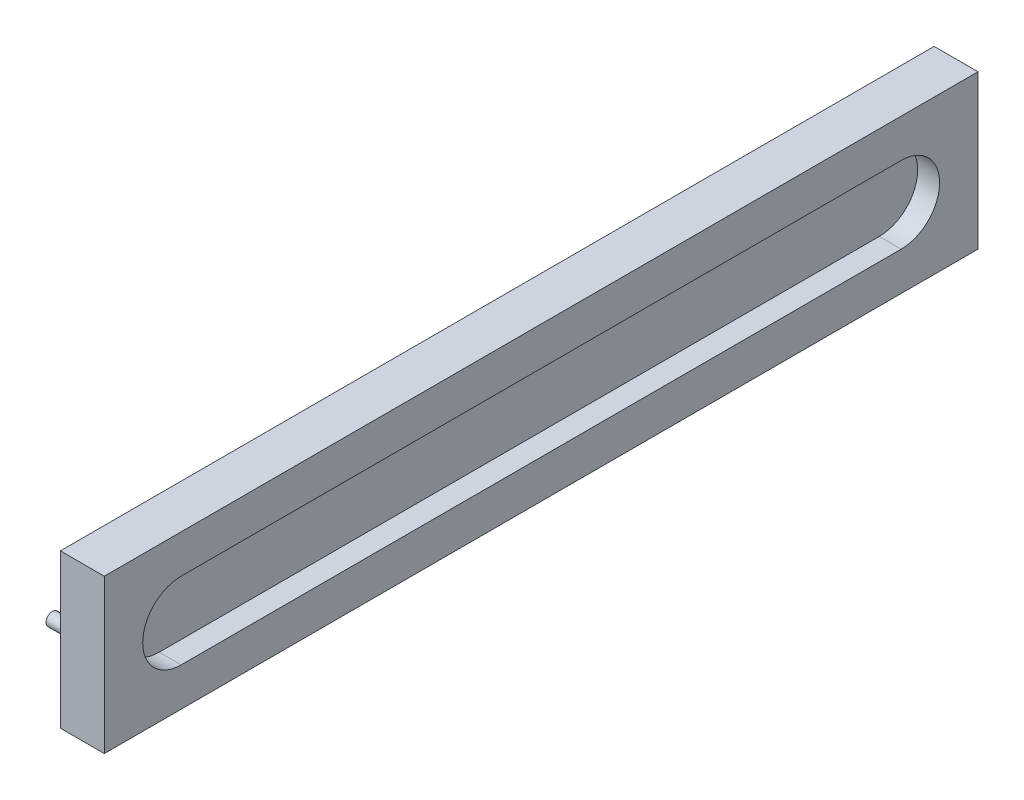
SolidWorks part; units mm, degrees
ref_plane "Front" through (0, 0, 0) normal (0, 0, 1) x (1, 0, 0)
ref_plane "Top" through (0, 0, 0) normal (0, 1, 0) x (1, 0, 0)
ref_plane "Right" through (0, 0, 0) normal (1, 0, 0) x (0, 0, -1)
sketch "Sketch2" plane through (0, 0, 0) normal (1, 0, 0) x (0, 0, -1)
  line L0 (0, 35) -> (17.5, 35) construction
  line L1 (0, 0) -> (398.1006, 0)
  line L2 (0, 0) -> (0, 70)
  line L3 (0, 70) -> (398.1006, 70)
  line L4 (398.1006, 0) -> (398.1006, 70)
  line L5 (17.5, 35) -> (35, 35) construction
  dimension "D1" = 70
  dimension "D2" = 17.5
  dimension "D3" = 17.5
extrude "Boss-Extrude1" add sketch "Sketch2" along normal blind 20
ref_plane "Plane1" through (20, 0, 0) normal (1, 0, 0) x (0, 0, -1)
sketch "Sketch3" plane through (20, 0, 0) normal (1, 0, 0) x (0, 0, -1)
  line L0 (0, 35) -> (17.5, 35) construction
  line L1 (0, 70) -> (0, 0) construction
  line L2 (17.5, 35) -> (35, 35) construction
  line L3 (35, 52.5) -> (363.1006, 52.5)
  line L4 (35, 17.5) -> (363.1006, 17.5)
  line L5 (199.0503, 0) -> (199.0503, 70) construction
  line L6 (0, 0) -> (398.1006, 0) construction
  line L7 (398.1006, 70) -> (0, 70) construction
  arc A0 (35, 52.5) -> (35, 17.5) centre (35, 35) ccw
  arc A1 (363.1006, 52.5) -> (363.1006, 17.5) centre (363.1006, 35) cw
  dimension "D1" = 17.5
extrude "Cut-Extrude1" cut sketch "Sketch3" against normal blind 10
sketch "Sketch4" plane through (0, 0, 0) normal (-1, 0, 0) x (0, 0, 1)
  line L0 (-398.1006, 35) -> (0, 35) construction
  line L1 (-398.1006, 0) -> (-398.1006, 70) construction
  line L2 (0, 70) -> (0, 0) construction
  line L3 (-199.0503, 70) -> (-199.0503, 0) construction
  line L4 (-398.1006, 70) -> (0, 70) construction
  line L5 (0, 0) -> (-398.1006, 0) construction
  circle A0 centre (-391.7506, 35) radius 2.921
  circle A1 centre (-6.35, 35) radius 2.921
  dimension "D1" = 5.842
  dimension "D2" = 6.35
  dimension "D3" = 385.4006
extrude "Boss-Extrude2" add sketch "Sketch4" along normal blind 10
